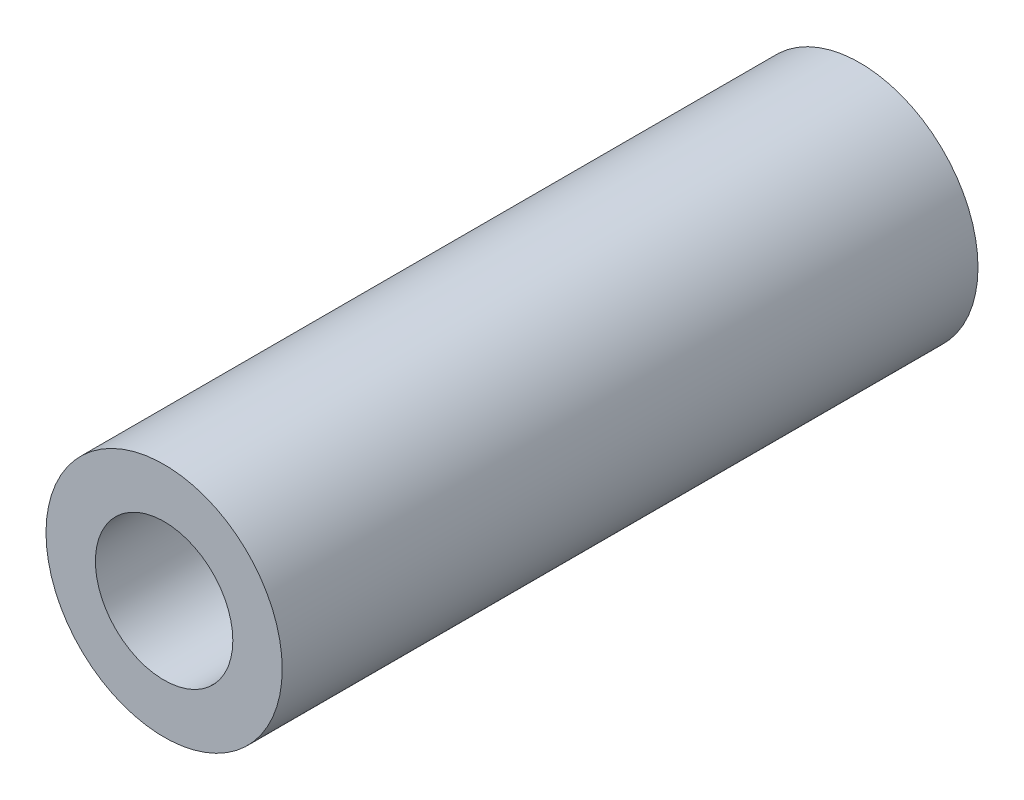
SolidWorks part; units mm, degrees
material "ABS"
ref_plane "正面" through (0, 0, 0) normal (0, 0, 1) x (1, 0, 0)
ref_plane "平面" through (0, 0, 0) normal (0, 1, 0) x (1, 0, 0)
ref_plane "右側面" through (0, 0, 0) normal (1, 0, 0) x (0, 0, -1)
sketch "ｽｹｯﾁ1" plane through (0, 0, 0) normal (0, 0, 1) x (1, 0, 0)
  circle A0 centre (0, 0) radius 1.6
  circle A1 centre (0, 0) radius 2.75
  dimension "D1" = 3.2
  dimension "D2" = 5.5
extrude "ﾎﾞｽ - 押し出し1" add sketch "ｽｹｯﾁ1" along normal blind 16.2
